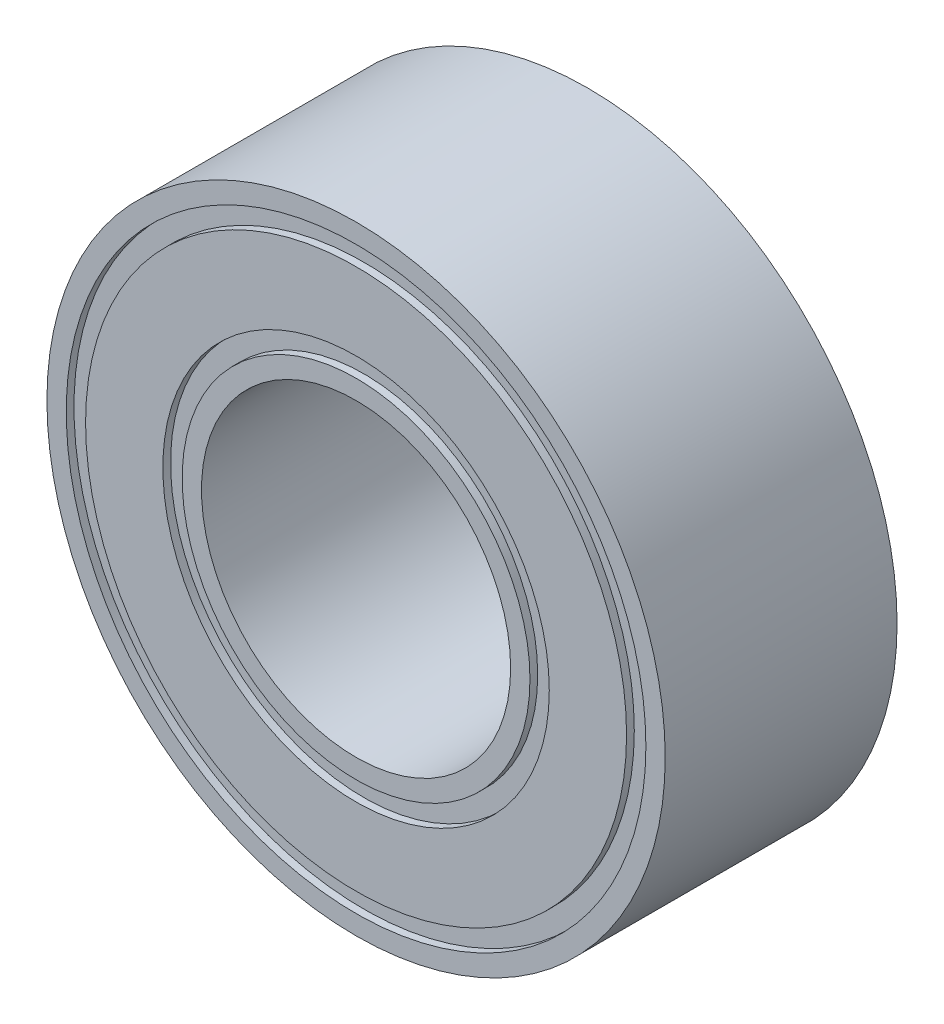
SolidWorks part; units mm, degrees
ref_plane "前视基准面" through (0, 0, 0) normal (0, 0, 1) x (1, 0, 0)
ref_plane "上视基准面" through (0, 0, 0) normal (0, 1, 0) x (1, 0, 0)
ref_plane "右视基准面" through (0, 0, 0) normal (1, 0, 0) x (0, 0, -1)
sketch "草图1" plane through (0, 0, 0) normal (0, 0, 1) x (1, 0, 0)
  circle A0 centre (0, 0) radius 4
  circle A1 centre (0, 0) radius 2
  dimension "D1" = 8
  dimension "D2" = 4
extrude "凸台-拉伸1" add sketch "草图1" along normal blind 3
sketch "草图2" plane through (0, 0, 3) normal (0, 0, 1) x (1, 0, 0)
  circle A0 centre (0, 0) radius 2.25
  circle A1 centre (0, 0) radius 2.5
  circle A2 centre (0, 0) radius 3.5
  circle A3 centre (0, 0) radius 3.75
  dimension "D1" = 7.5
  dimension "D2" = 7
  dimension "D3" = 4.5
  dimension "D4" = 5
extrude "切除-拉伸1" cut sketch "草图2" against normal blind 0.1 contours A3 A2 | A1 A0
sketch "草图3" plane through (0, 0, 0) normal (0, 0, -1) x (-1, 0, 0)
  circle A0 centre (0, 0) radius 2.25
  circle A1 centre (0, 0) radius 2.5
  circle A2 centre (0, 0) radius 3.5
  circle A3 centre (0, 0) radius 3.75
  dimension "D1" = 7.5
  dimension "D2" = 7
  dimension "D3" = 5
  dimension "D4" = 4.5
extrude "切除-拉伸2" cut sketch "草图3" against normal blind 0.1 contours A3 A2 | A1 A0
